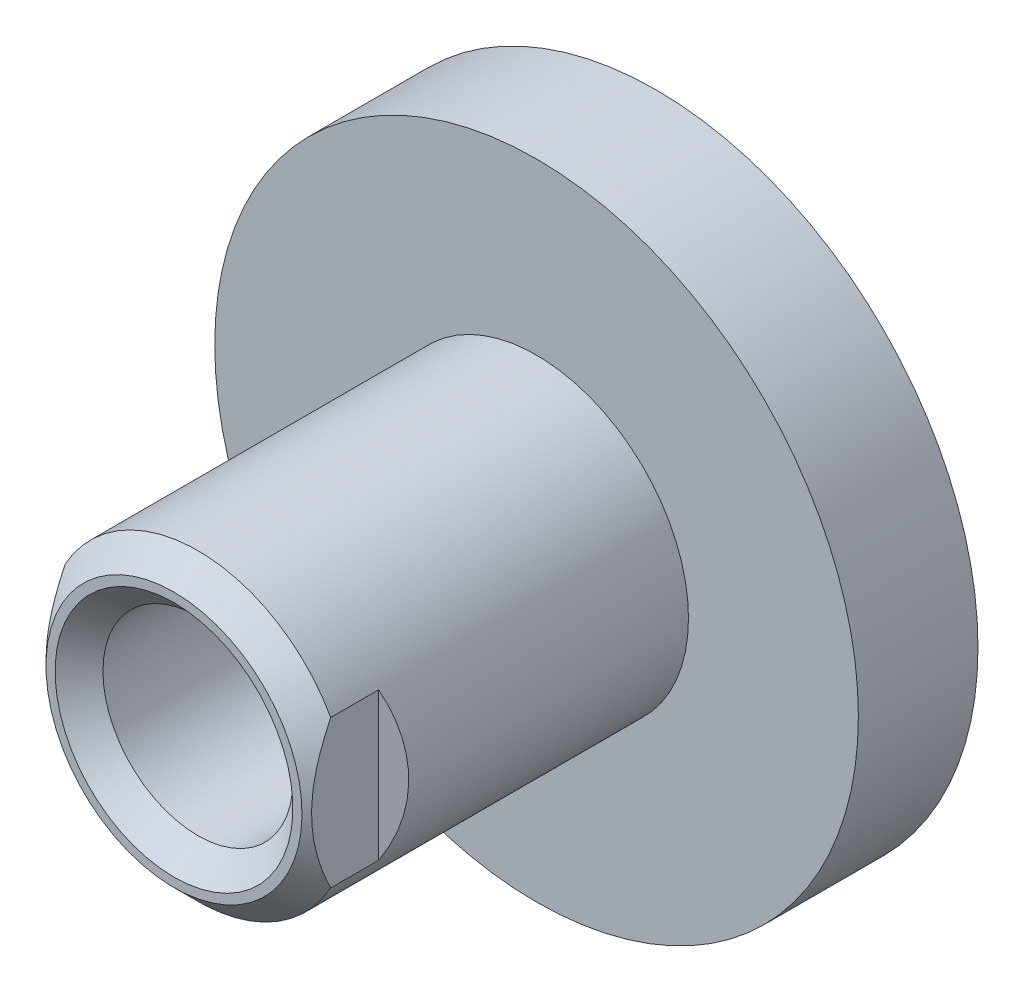
SolidWorks part; units mm, degrees
ref_plane "Front" through (0, 0, 0) normal (0, 0, 1) x (1, 0, 0)
ref_plane "Top" through (0, 0, 0) normal (0, 1, 0) x (1, 0, 0)
ref_plane "Right" through (0, 0, 0) normal (1, 0, 0) x (0, 0, -1)
sketch "Sketch1" plane through (0, 0, 0) normal (0, 0, 1) x (1, 0, 0)
  circle A0 centre (0, 0) radius 13.45
  dimension "D1" = 26.9
extrude "Piston" add sketch "Sketch1" along normal blind 5
sketch "Sketch2" plane through (0, 0, 0) normal (0, 0, -1) x (-1, 0, 0)
  circle A0 centre (0, 0) radius 6.35
  dimension "D1" = 12.7
extrude "Rod" add sketch "Sketch2" against normal up to surface (20.153 mm away)
sketch "Sketch8" plane through (0, 0, 20.153) normal (0, 0, 1) x (1, 0, 0)
  point P0 (0, 0)
hole_wizard "056 #8-32 Internal Thread" [suppressed] positions "3DSketch2" profile "Sketch9" tap size "#8-32" standard "Ansi Inch"
sketch3d "3DSketch2"
  point P0 (0, 0, 68.54)
sketch "Sketch9" plane through (0, 0, 68.54) normal (1, 0, 0) x (0, -1, 0)
  line L0 (0, 0) -> (0, 12.5378)
  line L1 (0, 12.5378) -> (1.7272, 11.5)
  line L2 (1.7272, 11.5) -> (1.7272, 9.144)
  line L3 (1.7272, 9.144) -> (2.0828, 9.144)
  line L4 (2.0828, 9.144) -> (2.0828, 0)
  line L5 (2.0828, 0) -> (0, 0)
  line L10 (0, 12.5378) -> (-1.7272, 11.5) construction
  line L11 (0, -6.35) -> (0, 107.95) construction
  dimension "Tap Drill Dia." = 3.4544
  dimension "Tap Drill Depth" = 11.5
  dimension "Thread Major Dia." = 4.1656
  dimension "Thread Depth" = 9.144
  dimension "Drill Angle" = 118
hole_wizard "075 #10-32 Internal Thread" [suppressed] positions "3DSketch3" profile "Sketch12" tap size "#10-32" standard "Ansi Inch"
sketch3d "3DSketch3"
  point P0 (0, 0, 50)
sketch "Sketch12" plane through (0, 0, 50) normal (1, 0, 0) x (0, -1, 0)
  line L0 (0, 0) -> (0, 15.2908)
  line L1 (0, 15.2908) -> (2.0193, 14.0774)
  line L2 (2.0193, 14.0774) -> (2.0193, 11.7)
  line L3 (2.0193, 11.7) -> (2.413, 11.7)
  line L4 (2.413, 11.7) -> (2.413, 0)
  line L5 (2.413, 0) -> (0, 0)
  line L10 (0, 15.2908) -> (-2.0193, 14.0774) construction
  line L11 (0, -6.35) -> (0, 107.95) construction
  dimension "Tap Drill Dia." = 4.0386
  dimension "Tap Drill Depth" = 11.5
  dimension "Thread Major Dia." = 4.826
  dimension "Thread Depth" = 9.144
  dimension "Drill Angle" = 118
hole_wizard "106 5/16-24 Internal Thread" positions "3DSketch4" profile "Sketch13" tap size "5/16-24" standard "Ansi Inch"
sketch3d "3DSketch4"
  point P0 (0, 0, 20.153)
sketch "Sketch13" plane through (0, 0, 20.153) normal (1, 0, 0) x (0, -1, 0)
  line L0 (0, 0) -> (0, 18.4532)
  line L1 (0, 18.4532) -> (3.4544, 16.3775)
  line L2 (3.4544, 16.3775) -> (3.4544, 13.208)
  line L3 (3.4544, 13.208) -> (3.9687, 13.208)
  line L4 (3.9687, 13.208) -> (3.9687, 0)
  line L5 (3.9687, 0) -> (0, 0)
  line L10 (0, 18.4532) -> (-3.4544, 16.3775) construction
  line L11 (0, -6.35) -> (0, 107.95) construction
  dimension "Tap Drill Dia." = 6.9088
  dimension "Tap Drill Depth" = 16.3775
  dimension "Thread Major Dia." = 7.9375
  dimension "Thread Depth" = 13.208
  dimension "Drill Angle" = 118
hole_wizard "150 3/8-24 Internal Thread" [suppressed] positions "3DSketch5" profile "Sketch14" tap size "3/8-24" standard "Ansi Inch"
sketch3d "3DSketch5"
  point P0 (0, 0, 50)
sketch "Sketch14" plane through (0, 0, 50) normal (1, 0, 0) x (0, -1, 0)
  line L0 (0, 0) -> (0, 18.411)
  line L1 (0, 18.411) -> (4.2164, 15.8775)
  line L2 (4.2164, 15.8775) -> (4.2164, 12.7)
  line L3 (4.2164, 12.7) -> (4.7625, 12.7)
  line L4 (4.7625, 12.7) -> (4.7625, 0)
  line L5 (4.7625, 0) -> (0, 0)
  line L10 (0, 18.411) -> (-4.2164, 15.8775) construction
  line L11 (0, -6.35) -> (0, 107.95) construction
  dimension "Tap Drill Dia." = 8.4328
  dimension "Tap Drill Depth" = 15.8775
  dimension "Thread Major Dia." = 9.525
  dimension "Thread Depth" = 12.7
  dimension "Drill Angle" = 118
hole_wizard "200-250 1/2-20 Internal Thread" [suppressed] positions "3DSketch6" profile "Sketch15" tap size "1/2-20" standard "Ansi Inch"
sketch3d "3DSketch6"
  point P0 (0, 0, 122.515)
sketch "Sketch15" plane through (0, 0, 122.515) normal (1, 0, 0) x (0, -1, 0)
  line L0 (0, 0) -> (0, 23.8576)
  line L1 (0, 23.8576) -> (5.7544, 20.4)
  line L2 (5.7544, 20.4) -> (5.7544, 17.78)
  line L3 (5.7544, 17.78) -> (6.35, 17.78)
  line L4 (6.35, 17.78) -> (6.35, 0)
  line L5 (6.35, 0) -> (0, 0)
  line L10 (0, 23.8576) -> (-5.7544, 20.4) construction
  line L11 (0, -6.35) -> (0, 107.95) construction
  dimension "Tap Drill Dia." = 11.5087
  dimension "Tap Drill Depth" = 15.01
  dimension "Thread Major Dia." = 12.7
  dimension "Thread Depth" = 11.176
  dimension "Drill Angle" = 118
chamfer "Rod End Chamfer" distance 1 angle 45 2 edges at (0, 6.35, 20.153) (0, -3.9687, 20.153)
sketch "Sketch11" plane through (0, 0, 0) normal (0, 1, 0) x (1, 0, 0)
  line L0 (0, -20.153) -> (0, -54.2319) construction
  line L1 (-5.55, -20.153) -> (-5.55, -17.153)
  line L2 (5.55, -20.153) -> (5.55, -17.153)
  line L3 (-5.55, -17.153) -> (-10.55, -14.2662)
  line L4 (5.55, -17.153) -> (10.55, -14.2662)
  line L5 (-10.55, -14.2662) -> (-10.55, -20.153)
  line L6 (10.55, -14.2662) -> (10.55, -20.153)
  line L7 (-10.55, -20.153) -> (-5.55, -20.153)
  line L8 (10.55, -20.153) -> (5.55, -20.153)
  line L9 (-6.35, -20.153) -> (6.35, -20.153) construction
  dimension "D1" = 60
  dimension "D2" = 5
  dimension "D3" = 3
  dimension "D4" = 11.1
extrude "Wrench Flats" cut sketch "Sketch11" against normal through all and the other way through all
sketch "Sketch16" plane through (0, 0, 20.153) normal (0, 0, 1) x (1, 0, 0)
  circle A0 centre (0, 0) radius 2.0828
  dimension "D1" = 4.1656
extrude "External Thread" [suppressed] add sketch "Sketch16" along normal blind 9.652
chamfer "External Rod Thread Chamfer" [suppressed] distance 0.3 angle 45
hole_wizard "300 5/8-18 Internal Thread" [suppressed] positions "3DSketch7" profile "Sketch17" tap size "5/8-18" standard "Ansi Inch"
sketch3d "3DSketch7"
  arc A0 (7.95, 3.0778, 122.515) -> (-7.95, 3.0778, 122.515) centre (0, 0, 122.515) ccw construction
  point P6 (0, 0, 122.515)
  point P15 (0, 0, 131.04)
sketch "Sketch17" plane through (0, 0, 122.515) normal (1, 0, 0) x (0, -1, 0)
  line L0 (0, 0) -> (0, 19.8164)
  line L1 (0, 19.8164) -> (7.3419, 15.405)
  line L2 (7.3419, 15.405) -> (7.3419, 11.176)
  line L3 (7.3419, 11.176) -> (7.9375, 11.176)
  line L4 (7.9375, 11.176) -> (7.9375, 0)
  line L5 (7.9375, 0) -> (0, 0)
  line L10 (0, 19.8164) -> (-7.3419, 15.405) construction
  line L11 (0, -6.35) -> (0, 107.95) construction
  dimension "Tap Drill Dia." = 14.6837
  dimension "Tap Drill Depth" = 15.405
  dimension "Thread Major Dia." = 15.875
  dimension "Thread Depth" = 11.176
  dimension "Drill Angle" = 118
hole_wizard "400 3/4-16 Internal Thread" [suppressed] positions "3DSketch8" profile "Sketch18" tap size "3/4-16" standard "Ansi Inch"
sketch3d "3DSketch8"
  arc A0 (11.176, 3.4622, 122.515) -> (-11.176, 3.4622, 122.515) centre (0, 0, 122.515) ccw construction
  point P0 (0, 0, 122.515)
  point P9 (0, 0, 134.215)
sketch "Sketch18" plane through (0, 0, 122.515) normal (1, 0, 0) x (0, -1, 0)
  line L0 (0, 0) -> (0, 21.7563)
  line L1 (0, 21.7563) -> (8.7312, 16.51)
  line L2 (8.7312, 16.51) -> (8.7312, 16.448)
  line L3 (8.7312, 16.448) -> (9.525, 16.448)
  line L4 (9.525, 16.448) -> (9.525, 0)
  line L5 (9.525, 0) -> (0, 0)
  line L10 (0, 21.7563) -> (-8.7313, 16.51) construction
  line L11 (0, -6.35) -> (0, 107.95) construction
  dimension "Tap Drill Dia." = 17.4625
  dimension "Tap Drill Depth" = 16.51
  dimension "Thread Major Dia." = 19.05
  dimension "Thread Depth" = 16.448
  dimension "Drill Angle" = 118
